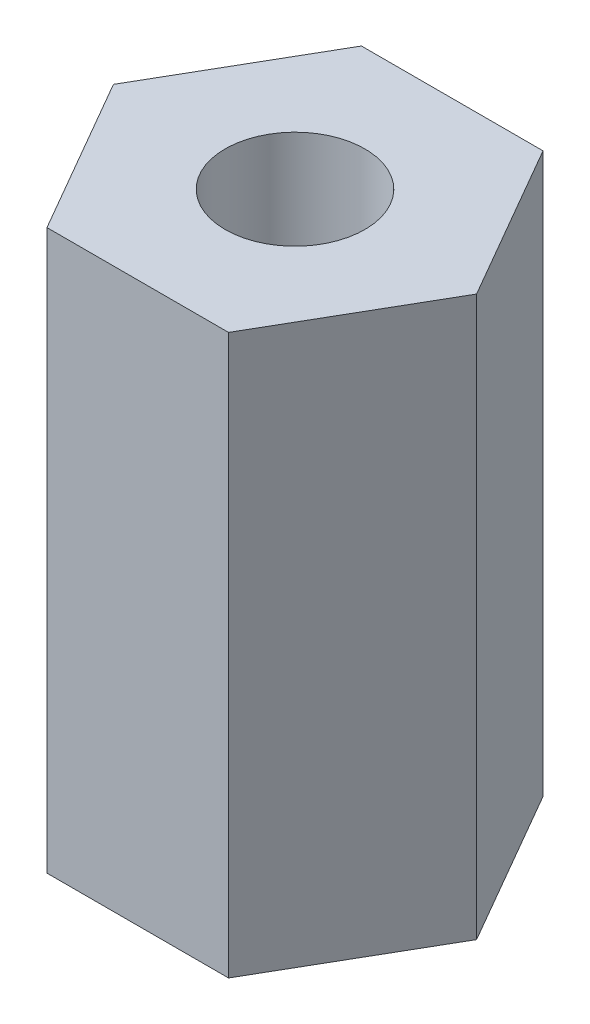
SolidWorks part; units mm, degrees
material "PA Type 6"
ref_plane "Front Plane" through (0, 0, 0) normal (0, 0, 1) x (1, 0, 0)
ref_plane "Top Plane" through (0, 0, 0) normal (0, 1, 0) x (1, 0, 0)
ref_plane "Right Plane" through (0, 0, 0) normal (1, 0, 0) x (0, 0, -1)
sketch "Sketch1" plane through (0, 0, 0) normal (0, 1, 0) x (1, 0, 0)
  line L1 (1.6498, -2.8575) -> (3.2996, 0)
  line L2 (3.2996, 0) -> (1.6498, 2.8575)
  line L3 (1.6498, 2.8575) -> (-1.6498, 2.8575)
  line L4 (-1.6498, 2.8575) -> (-3.2996, 0)
  line L5 (-3.2996, 0) -> (-1.6498, -2.8575)
  line L6 (-1.6498, -2.8575) -> (1.6498, -2.8575)
  circle A0 centre (0, 0) radius 2.8575 construction
  circle A1 centre (0, 0) radius 1.27
  dimension "D1" = 2.54
  dimension "D2" = 5.715
extrude "Boss-Extrude1" add sketch "Sketch1" along normal mid plane 10.16
